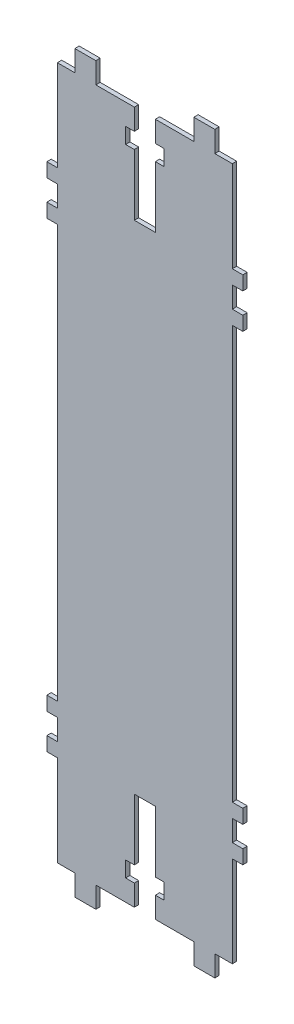
SolidWorks part; units mm, degrees
ref_plane "Front Plane" through (0, 0, 0) normal (0, 0, 1) x (1, 0, 0)
ref_plane "Top Plane" through (0, 0, 0) normal (0, 1, 0) x (1, 0, 0)
ref_plane "Right Plane" through (0, 0, 0) normal (1, 0, 0) x (0, 0, -1)
sketch "Sketch1" plane through (0, 0, 0) normal (0, 0, 1) x (1, 0, 0)
  line L3 (70.155, 166.9753) -> (70.155, 176.6563)
  line L4 (70.155, 176.6563) -> (62.895, 176.6563)
  line L5 (62.895, 176.6563) -> (62.895, 239.583)
  line L6 (62.895, 239.583) -> (50.7979, 239.583)
  line L7 (50.7979, 239.583) -> (50.7979, 254.1029)
  line L8 (50.7979, 254.1029) -> (36.278, 254.1029)
  line L9 (36.278, 254.1029) -> (36.278, 239.583)
  line L10 (36.278, 239.583) -> (9.6544, 239.583)
  line L11 (9.6544, 239.583) -> (9.6544, 225.0598)
  line L12 (9.6544, 225.0598) -> (15.7037, 225.0598)
  line L13 (15.7037, 225.0598) -> (15.7037, 214.1999)
  line L14 (15.7037, 214.1999) -> (9.6544, 214.1999)
  line L15 (9.6544, 214.1999) -> (9.6544, 171.8158)
  line L16 (9.6544, 171.8158) -> (-4.8672, 171.8158)
  line L17 (-4.8672, 171.8158) -> (-4.8672, 214.1999)
  line L18 (-4.8672, 214.1999) -> (-10.9166, 214.1999)
  line L19 (-10.9166, 214.1999) -> (-10.9166, 225.0598)
  line L20 (-10.9166, 225.0598) -> (-4.8672, 225.0598)
  line L21 (-4.8672, 225.0598) -> (-4.8672, 239.583)
  line L22 (-4.8672, 239.583) -> (-31.4842, 239.583)
  line L23 (-31.4842, 239.583) -> (-31.4842, 254.1029)
  line L24 (-31.4842, 254.1029) -> (-46.0041, 254.1029)
  line L25 (-46.0041, 254.1029) -> (-46.0041, 239.583)
  line L26 (-46.0041, 239.583) -> (-58.1029, 239.583)
  line L27 (-58.1029, 239.583) -> (-58.1029, 176.6563)
  line L28 (-58.1029, 176.6563) -> (-65.3628, 176.6563)
  line L29 (-65.3628, 176.6563) -> (-65.3628, 166.9753)
  line L30 (-65.3628, 166.9753) -> (-58.1029, 166.9753)
  line L31 (-58.1029, 166.9753) -> (-58.1029, 152.4554)
  line L32 (-58.1029, 152.4554) -> (-65.3628, 152.4554)
  line L33 (-65.3628, 152.4554) -> (-65.3628, 142.776)
  line L34 (-65.3628, 142.776) -> (-58.1029, 142.776)
  line L35 (-58.1029, 142.776) -> (-58.1029, -142.7844)
  line L36 (-58.1029, -142.7844) -> (-65.3628, -142.7844)
  line L37 (-65.3628, -142.7844) -> (-65.3628, -152.4654)
  line L38 (-65.3628, -152.4654) -> (-58.1029, -152.4654)
  line L39 (-58.1029, -152.4654) -> (-58.1029, -166.9853)
  line L40 (-58.1029, -166.9853) -> (-65.3628, -166.9853)
  line L41 (-65.3628, -166.9853) -> (-65.3628, -176.6613)
  line L42 (-65.3628, -176.6613) -> (-58.1029, -176.6613)
  line L43 (-58.1029, -176.6613) -> (-58.1029, -239.5797)
  line L44 (-58.1029, -239.5797) -> (-46.0041, -239.5797)
  line L45 (-46.0041, -239.5797) -> (-46.0041, -254.1029)
  line L46 (-46.0041, -254.1029) -> (-31.4842, -254.1029)
  line L47 (-31.4842, -254.1029) -> (-31.4842, -239.583)
  line L48 (-31.4842, -239.583) -> (-4.8672, -239.583)
  line L49 (-4.8672, -239.583) -> (-4.8672, -225.0631)
  line L50 (-4.8672, -225.0631) -> (-10.9166, -225.0631)
  line L51 (-10.9166, -225.0631) -> (-10.9166, -214.2182)
  line L52 (-10.9166, -214.2182) -> (-4.8672, -214.2182)
  line L53 (-4.8672, -214.2182) -> (-4.8672, -171.8241)
  line L54 (-4.8672, -171.8241) -> (9.6544, -171.8241)
  line L55 (9.6544, -171.8241) -> (9.6544, -214.2182)
  line L56 (9.6544, -214.2182) -> (15.7037, -214.2182)
  line L57 (15.7037, -214.2182) -> (15.7037, -225.0631)
  line L58 (15.7037, -225.0631) -> (9.6544, -225.0631)
  line L59 (9.6544, -225.0631) -> (9.6544, -239.583)
  line L60 (9.6544, -239.583) -> (36.278, -239.583)
  line L61 (36.278, -239.583) -> (36.278, -254.1029)
  line L62 (36.278, -254.1029) -> (50.7979, -254.1029)
  line L63 (50.7979, -254.1029) -> (50.7979, -239.5797)
  line L64 (50.7979, -239.5797) -> (62.895, -239.5797)
  line L65 (62.895, -239.5797) -> (62.895, -176.6613)
  line L66 (62.895, -176.6613) -> (70.155, -176.6613)
  line L67 (70.155, -176.6613) -> (70.155, -166.9853)
  line L68 (70.155, -166.9853) -> (62.895, -166.9853)
  line L69 (62.895, -166.9853) -> (62.895, -152.4654)
  line L70 (62.895, -152.4654) -> (70.155, -152.4654)
  line L71 (70.155, -152.4654) -> (70.155, -142.7844)
  line L72 (70.155, -142.7844) -> (62.895, -142.7844)
  line L73 (62.895, -142.7844) -> (62.895, 142.776)
  line L74 (62.895, 142.776) -> (70.155, 142.776)
  line L75 (70.155, 142.776) -> (70.155, 152.4554)
  line L76 (70.155, 152.4554) -> (62.895, 152.4554)
  line L77 (62.895, 152.4554) -> (62.895, 166.9753)
  line L78 (62.895, 166.9753) -> (70.155, 166.9753)
extrude "Boss-Extrude1" add sketch "Sketch1" along normal blind 3
